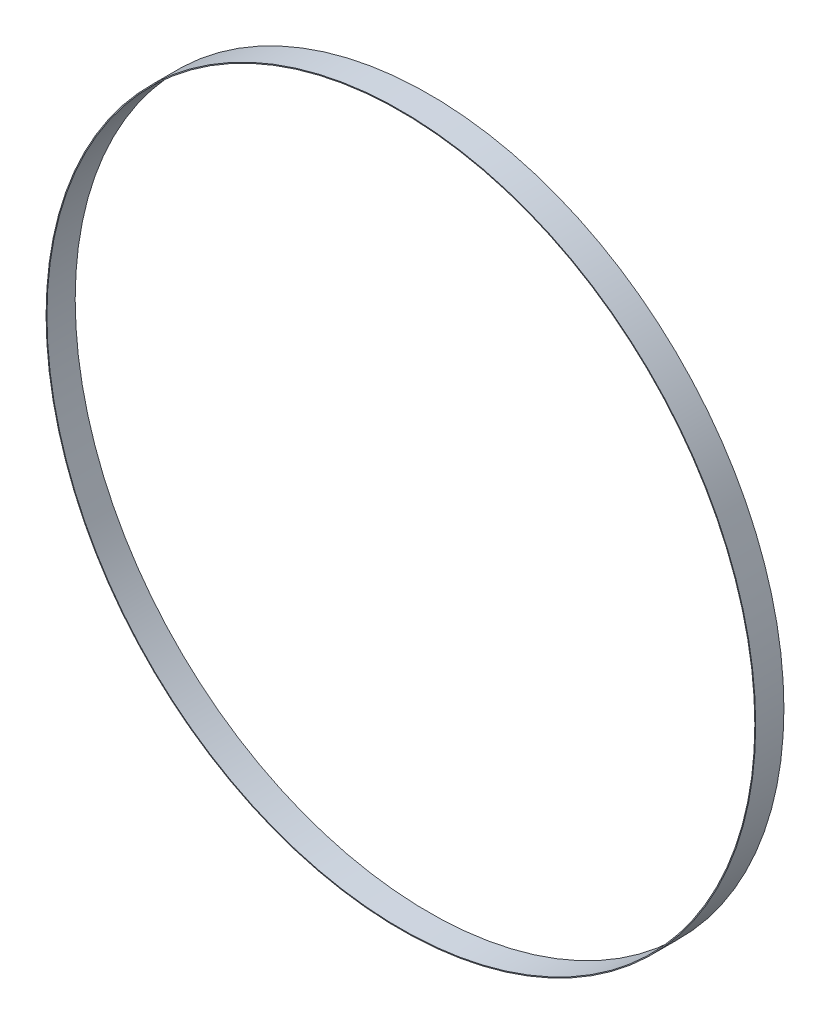
SolidWorks part; units mm, degrees
ref_plane "Front Plane" through (0, 0, 0) normal (0, 0, 1) x (1, 0, 0)
ref_plane "Top Plane" through (0, 0, 0) normal (0, 1, 0) x (1, 0, 0)
ref_plane "Right Plane" through (0, 0, 0) normal (1, 0, 0) x (0, 0, -1)
sketch "Sketch1" plane through (0, 0, 0) normal (0, 0, 1) x (1, 0, 0)
  circle A0 centre (0, 0) radius 1253
  circle A1 centre (0, 0) radius 1256
  dimension "D1" = 2506
  dimension "D2" = 3
extrude "Boss-Extrude1" add sketch "Sketch1" along normal blind 100
